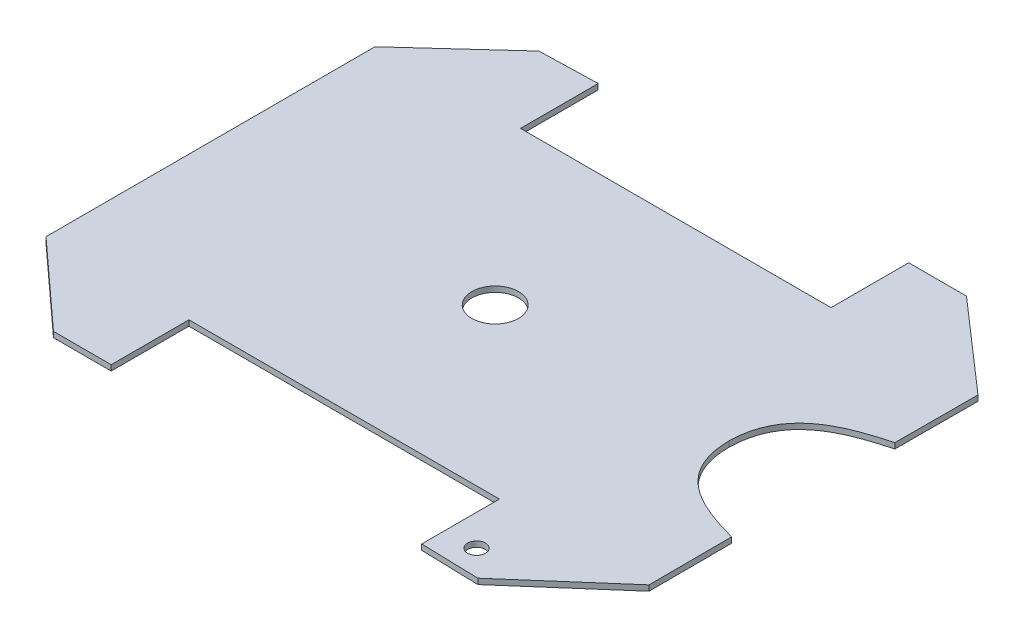
SolidWorks part; units mm, degrees
ref_plane "Спереди" through (0, 0, 0) normal (0, 0, 1) x (1, 0, 0)
ref_plane "Сверху" through (0, 0, 0) normal (0, 1, 0) x (1, 0, 0)
ref_plane "Справа" through (0, 0, 0) normal (1, 0, 0) x (0, 0, -1)
sketch "Эскиз1" plane through (0, 0, 0) normal (0, 1, 0) x (1, 0, 0)
  line L1 (-269.7922, 73.2626) -> (-269.7922, -223.012)
  line L2 (139.0683, -293.4928) -> (191.0683, -294.8909)
  line L3 (-140.5865, 145.1415) -> (-192.5865, 143.7434)
  line L4 (139.0683, -223.4928) -> (139.0683, -293.4928)
  line L5 (139.0683, 145.1415) -> (191.0683, 145.1415)
  line L6 (-140.5865, 75.1415) -> (-140.5865, 145.1415)
  line L7 (-0.7591, -12.2026) -> (-0.7591, 227.1905) construction
  line L8 (273.3416, 73.2626) -> (273.1017, -1.3674)
  line L9 (-140.5865, -223.4928) -> (139.0683, -223.4928)
  line L10 (139.0683, 75.1415) -> (139.0683, 145.1415)
  line L11 (-140.5865, 75.1415) -> (139.0683, 75.1415)
  line L12 (-140.5865, -223.4928) -> (-140.5865, -293.4928)
  line L13 (-140.5865, -293.4928) -> (-192.5865, -293.4928)
  line L14 (273.3416, -223.012) -> (273.1017, -148.382)
  line L17 (-326.8393, -74.8747) -> (107.7018, -74.8747) construction
  line L22 (-269.7922, 73.2626) -> (-192.5865, 143.7434)
  line L23 (-269.7922, -223.012) -> (-192.5865, -293.4928)
  line L24 (-263.7922, 73.2626) -> (-387.0064, 73.2626) construction
  line L25 (-269.7922, -223.012) -> (-392.2998, -223.012) construction
  line L26 (273.3416, -223.012) -> (191.0683, -294.8909)
  line L27 (273.3416, 73.2626) -> (191.0683, 145.1415)
  spline S0 degree 3 poles (273.1017, -1.3674) (239.3639, -10.6036) (197.437, -24.3257) (197.0474, -74.8747) knots 0 0 0 0 1 1 1 1
  spline S1 degree 3 poles (241.301, -16.5) (241.3128, -13.4345) (241.3008, -5.6967) (241.2828, -4.7983) knots 0 0 0 0 1 1 1 1 weights 1 0.504087 0.504087 1 construction
  spline S2 degree 3 poles (273.1017, -148.382) (239.3639, -139.1459) (197.437, -125.4237) (197.0474, -74.8747) knots 0 0 0 0 1 1 1 1
extrude "Вытянуть1" add sketch "Эскиз1" along normal blind 5
sketch "Эскиз2" plane through (0, 5, 0) normal (0, 1, 0) x (-1, 0, 0)
  circle A0 centre (14.23, 74.0267) radius 21
extrude "Вырез-Вытянуть1" cut sketch "Эскиз2" against normal through all
sketch "Sketch1" plane through (0, 5, 0) normal (0, 1, 0) x (1, 0, 0)
  circle A0 centre (167.053, -272.0659) radius 8
extrude "Cut-Extrude1" cut sketch "Sketch1" against normal through all
